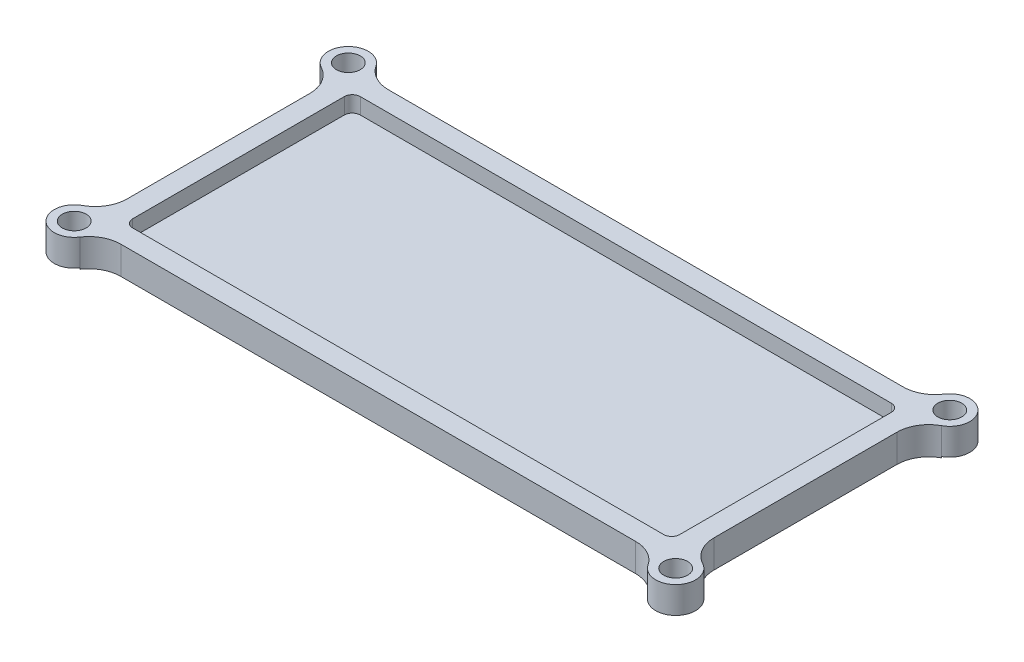
SolidWorks part; units mm, degrees
ref_plane "Front Plane" through (0, 0, 0) normal (0, 0, 1) x (1, 0, 0)
ref_plane "Top Plane" through (0, 0, 0) normal (0, 1, 0) x (1, 0, 0)
ref_plane "Right Plane" through (0, 0, 0) normal (1, 0, 0) x (0, 0, -1)
sketch "Sketch1" plane through (0, 0, 0) normal (0, 1, 0) x (1, 0, 0)
  line L0 (-35.25, 15.25) -> (-36.75, 15.25) construction
  line L1 (35.25, 15.25) -> (-35.25, 15.25)
  line L2 (35.25, 15.25) -> (35.25, -15.25)
  line L3 (35.25, -15.25) -> (-35.25, -15.25)
  line L4 (-35.25, 15.25) -> (-35.25, -15.25)
  line L5 (35.25, 15.25) -> (-35.25, -15.25) construction
  line L6 (35.25, -15.25) -> (-35.25, 15.25) construction
  line L7 (36.75, 16.75) -> (-36.75, 16.75)
  line L8 (36.75, 16.75) -> (36.75, -16.75)
  line L9 (36.75, -16.75) -> (-36.75, -16.75)
  line L10 (-36.75, 16.75) -> (-36.75, -16.75)
  line L11 (36.75, 16.75) -> (-36.75, -16.75) construction
  line L12 (36.75, -16.75) -> (-36.75, 16.75) construction
  line L13 (-35.25, 15.25) -> (-35.25, 16.75) construction
  line L14 (0, 16.75) -> (0, -16.75) construction
  line L15 (-36.75, 0) -> (36.5, 0) construction
  line L16 (-38.6599, 17.1647) -> (-40.1599, 17.1647) construction
  circle A0 centre (-37.6599, 17.1647) radius 1
  circle A1 centre (-37.6599, 17.1647) radius 2.5
  circle A2 centre (37.6599, 17.1647) radius 2.5
  circle A3 centre (37.6599, 17.1647) radius 1
  circle A4 centre (37.6599, -17.1647) radius 1
  circle A5 centre (37.6599, -17.1647) radius 2.5
  circle A6 centre (-37.6599, -17.1647) radius 2.5
  circle A7 centre (-37.6599, -17.1647) radius 1
  point P0 (0, 0)
  point P6 (0, 0)
  dimension "D4" = 2
  dimension "D1" = 30.5
  dimension "D2" = 70.5
  dimension "D3" = 1.5
extrude "Boss-Extrude1" add sketch "Sketch1" along normal blind 1.5 contours L1 L4 L3 L2 | L10 A6 L9 A5 L8 A2 L7 A1 L4 L1 L2 L3 | L10 A1 L7 | L7 A1 L10 A0 | L9 A7 L10 A6 | A6 L10 L9 | L8 A5 L9 | L9 A5 L8 A4 | A2 L8 L7 | L7 A3 L8 A2
sketch "Sketch2" plane through (0, 1.5, 0) normal (0, 1, 0) x (1, 0, 0)
  line L0 (34.25, -14.25) -> (34.25, 14.25)
  line L1 (34.25, 14.25) -> (-34.25, 14.25)
  line L2 (-34.25, 14.25) -> (-34.25, -14.25)
  line L3 (-34.25, -14.25) -> (34.25, -14.25)
  line L4 (36.75, -14.8362) -> (36.75, 14.8362)
  line L5 (35.1946, 16.75) -> (-35.1946, 16.75)
  line L6 (-36.75, 14.8362) -> (-36.75, -14.8362)
  line L7 (-35.1946, -16.75) -> (35.1946, -16.75)
  line L8 (36.75, -14.8362) -> (36.75, 14.8362)
  line L9 (35.1946, 16.75) -> (-35.1946, 16.75)
  line L10 (-36.75, 14.8362) -> (-36.75, -14.8362)
  line L11 (-35.1946, -16.75) -> (35.1946, -16.75)
  arc A0 (34.25, 14.25) -> (34.25, 14.25) centre (34.25, 14.25) ccw
  arc A1 (-34.25, 14.25) -> (-34.25, 14.25) centre (-34.25, 14.25) ccw
  arc A2 (-34.25, -14.25) -> (-34.25, -14.25) centre (-34.25, -14.25) ccw
  arc A3 (34.25, -14.25) -> (34.25, -14.25) centre (34.25, -14.25) ccw
  arc A4 (36.75, 14.8362) -> (35.1946, 16.75) centre (37.6599, 17.1647) ccw
  arc A5 (-35.1946, 16.75) -> (-36.75, 14.8362) centre (-37.6599, 17.1647) ccw
  arc A6 (-36.75, -14.8362) -> (-35.1946, -16.75) centre (-37.6599, -17.1647) ccw
  arc A7 (35.1946, -16.75) -> (36.75, -14.8362) centre (37.6599, -17.1647) ccw
  arc A8 (36.75, 14.8362) -> (35.1946, 16.75) centre (37.6599, 17.1647) ccw
  arc A9 (-35.1946, 16.75) -> (-36.75, 14.8362) centre (-37.6599, 17.1647) ccw
  arc A10 (-36.75, -14.8362) -> (-35.1946, -16.75) centre (-37.6599, -17.1647) ccw
  arc A11 (35.1946, -16.75) -> (36.75, -14.8362) centre (37.6599, -17.1647) ccw
  circle A12 centre (37.6599, -17.1647) radius 1 construction
  circle A13 centre (37.6599, 17.1647) radius 1 construction
  circle A14 centre (-37.6599, 17.1647) radius 1 construction
  circle A15 centre (-37.6599, -17.1647) radius 1 construction
  circle A16 centre (37.6599, -17.1647) radius 1
  circle A17 centre (37.6599, 17.1647) radius 1
  circle A18 centre (-37.6599, 17.1647) radius 1
  circle A19 centre (-37.6599, -17.1647) radius 1
  dimension "D1" = 0
  dimension "D2" = 2.5
extrude "Boss-Extrude2" add sketch "Sketch2" along normal blind 2
fillet "Fillet1" radius 4 8 edges at (36.75, 1.75, -14.8362) (-35.1946, 1.75, -16.75) (36.75, 1.75, 14.8362) (-36.75, 1.75, -14.8362) (35.1946, 1.75, -16.75) (-36.75, 1.75, 14.8362) (35.1946, 1.75, 16.75) (-35.1946, 1.75, 16.75)
hole_wizard "CSK for M2.5 Flat Head Machine Screw1" positions "Sketch5" profile "Sketch6" countersink size "M2.5" standard "ANSI Metric" end condition through all
sketch "Sketch5" plane through (0, 0, 0) normal (0, -1, 0) x (-1, 0, 0)
  point P0 (37.6599, -17.1647)
  point P3 (37.6599, 17.1647)
  point P6 (-37.6599, -17.1647)
  point P9 (-37.6599, 17.1647)
sketch "Sketch6" plane through (-37.6599, 0, 17.1647) normal (1, 0, 0) x (0, 0, -1)
  line L0 (0, 0) -> (0, 3.5)
  line L1 (0, 3.5) -> (1.5, 3.5)
  line L2 (1.5, 3.5) -> (1.5, 1.15)
  line L3 (1.5, 1.15) -> (2.5, 0.15)
  line L4 (2.5, 0.15) -> (2.5, 0)
  line L6 (2.5, 0) -> (0, 0)
  line L7 (-1.5, 1.15) -> (-2.5, 0.15) construction
  line L11 (0, -6.35) -> (0, 107.95) construction
  dimension "Thru Hole Dia." = 3
  dimension "Thru Hole Depth" = 3.5
  dimension "C'Sink Dia." = 5
  dimension "C'Sink Angle" = 90
  dimension "Head Clearance" = 0.15
fillet "Fillet2" radius 1 4 edges at (-34.25, 2.5, 14.25) (34.25, 2.5, 14.25) (-34.25, 2.5, -14.25) (34.25, 2.5, -14.25)
